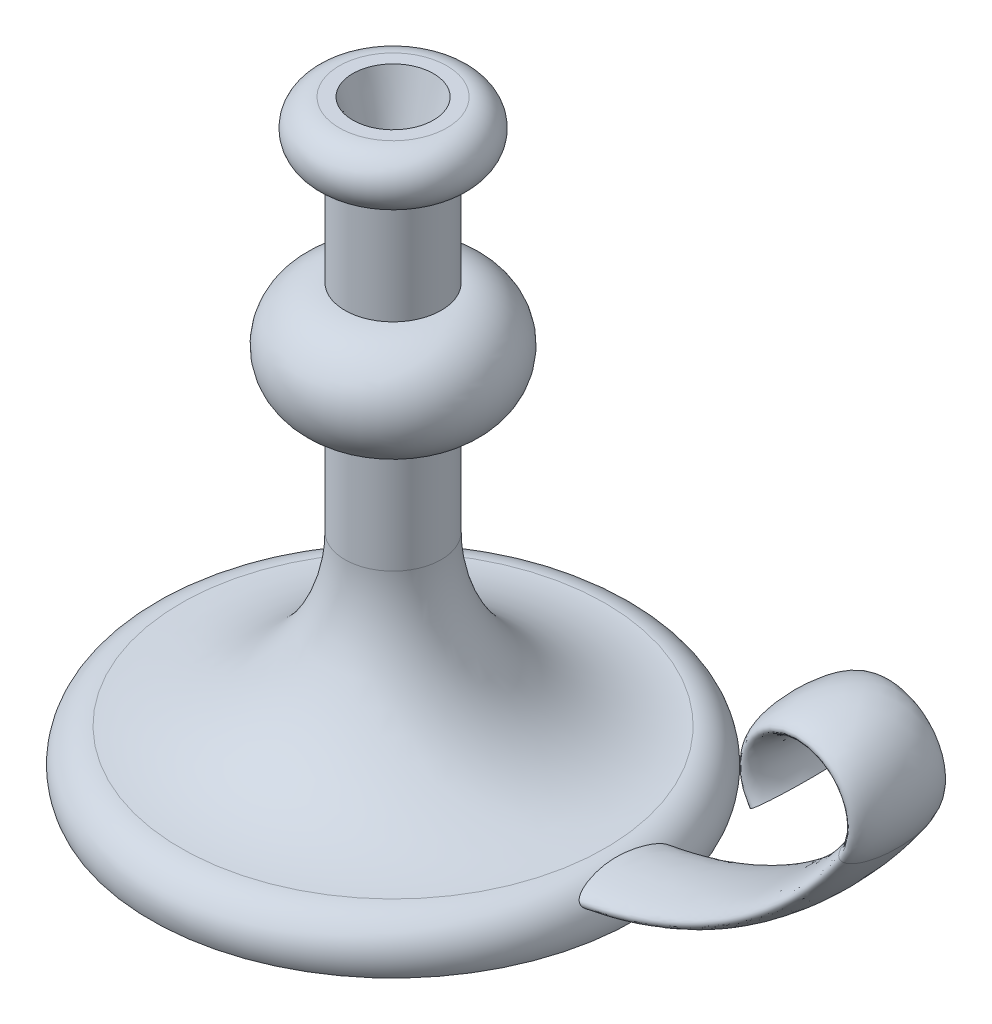
SolidWorks part; units mm, degrees
ref_plane "Front Plane" through (0, 0, 0) normal (0, 0, 1) x (1, 0, 0)
ref_plane "Top Plane" through (0, 0, 0) normal (0, 1, 0) x (1, 0, 0)
ref_plane "Right Plane" through (0, 0, 0) normal (1, 0, 0) x (0, 0, -1)
sketch "Sketch1" plane through (0, 0, 0) normal (0, 0, 1) x (1, 0, 0)
  line L0 (0, 0) -> (0, 220)
  line L1 (20, 220) -> (0, 220)
  line L2 (0, 0) -> (90, 0)
  line L3 (17.9064, 200.2216) -> (17.9064, 160.2216)
  line L4 (17.9064, 120.227) -> (17.9064, 80)
  arc A0 (20, 220) -> (17.9064, 200.2216) centre (20, 210) cw
  arc A1 (17.9064, 160.2216) -> (17.9064, 120.227) centre (17.5792, 140.2243) cw
  arc A2 (17.9064, 80) -> (78.8777, 17.5959) centre (80.3273, 80) ccw
  arc A3 (78.8777, 17.5959) -> (90, 0) centre (78.5874, 5.0993) cw
  dimension "D4" = 10
  dimension "D6" = 20
  dimension "D5" = 12.5
  dimension "D1" = 220
  dimension "D2" = 20
  dimension "D3" = 90
  dimension "D7" = 40
  dimension "D8" = 80
revolve "Revolve1" add sketch "Sketch1" angle 360 about L0
sketch "Sketch3" plane through (0, 0, 0) normal (0, 0, 1) x (1, 0, 0)
  line L0 (0, 10) -> (60, 10)
  line L2 (0, 227.4356) -> (0, 175.1288) construction
  line L3 (0, 162.9374) -> (0, 94.798) construction
  line L4 (0, 200.2216) -> (0, 160.2216) construction
  line L5 (0, 126.3326) -> (0, -12.6653) construction
  line L6 (-90, 0) -> (90, 0) construction
  arc A0 (60, 10) -> (183.5921, 75) centre (60, 160) ccw
  arc A1 (183.5921, 75) -> (150.6342, 75) centre (167.1131, 86.3333) ccw
  point P9 (0, 7.1542)
  point P14 (0, 8.7506)
  dimension "D2" = 150
  dimension "D4" = 20
  dimension "D1" = 60
  dimension "D3" = 65
  dimension "D5" = 10
sketch "Sketch4" plane through (0, 0, 0) normal (1, 0, 0) x (0, 0, -1)
  ellipse E0 centre (0, 10) end of major axis (17.5, 10) minor radius 5
  point P1 (0, 10)
  point P7 (0, 10)
  dimension "D1" = 35
  dimension "D2" = 10
sweep "Sweep1" add profiles "Sketch4" path "Sketch3"
sketch "Sketch7" plane through (0, 220, 0) normal (0, 1, 0) x (1, 0, 0)
  circle A0 centre (0, 0) radius 15
  dimension "D1" = 30
extrude "Cut-Extrude3" cut sketch "Sketch7" against normal blind 25 draft 15 contours A0
